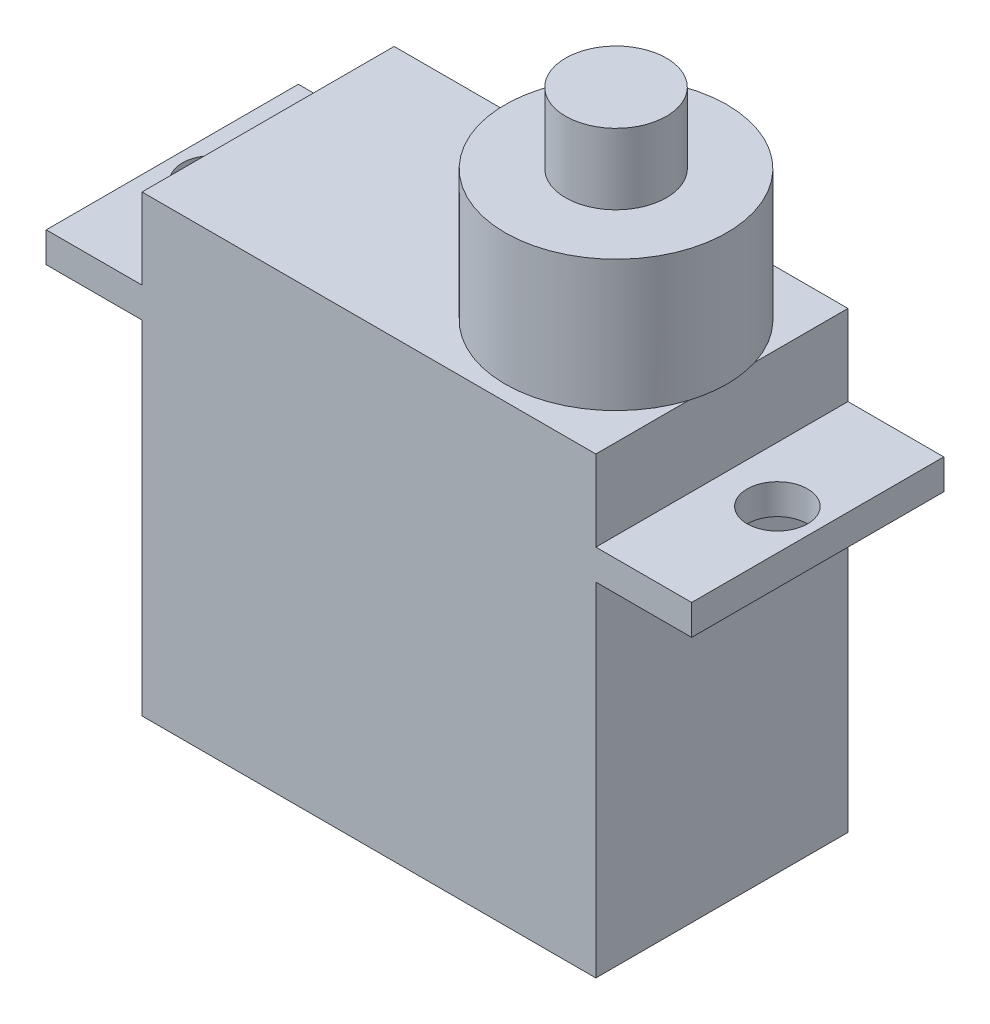
SolidWorks part; units mm, degrees
ref_plane "前视基准面" through (0, 0, 0) normal (0, 0, 1) x (1, 0, 0)
ref_plane "上视基准面" through (0, 0, 0) normal (0, 1, 0) x (1, 0, 0)
ref_plane "右视基准面" through (0, 0, 0) normal (1, 0, 0) x (0, 0, -1)
sketch "草图1" plane through (0, 0, 0) normal (0, 1, 0) x (1, 0, 0)
  line L1 (0, 0) -> (22.5, 0)
  line L2 (0, 0) -> (0, -12.5)
  line L3 (0, -12.5) -> (22.5, -12.5)
  line L4 (22.5, 0) -> (22.5, -12.5)
  dimension "D1" = 12.5
  dimension "D2" = 22.5
extrude "凸台-拉伸1" add sketch "草图1" along normal blind 17
sketch "草图2" plane through (0, 17, 0) normal (0, 1, 0) x (1, 0, 0)
  line L0 (0, -12.5) -> (22.5, -12.5) construction
  line L1 (-4.75, 0) -> (27.25, 0)
  line L2 (-4.75, 0) -> (-4.75, -12.5)
  line L3 (-4.75, -12.5) -> (27.25, -12.5)
  line L4 (27.25, 0) -> (27.25, -12.5)
  line L5 (-4.75, 0) -> (27.25, -12.5) construction
  line L6 (-4.75, -12.5) -> (27.25, 0) construction
  line L7 (22.5, 0) -> (0, 0) construction
  line L8 (0, -6.25) -> (27.25, -6.25) construction
  line L9 (11.25, 0) -> (11.25, -6.25) construction
  line L10 (0, 0) -> (0, -12.5) construction
  circle A0 centre (-2.75, -6.25) radius 1.5
  circle A2 centre (25.25, -6.25) radius 1.5
  point P0 (11.25, -6.25)
  point P7 (0, 0)
  dimension "D4" = 3
  dimension "D1" = 32
  dimension "D2" = 28
extrude "凸台-拉伸2" add sketch "草图2" along normal blind 1.5
sketch "草图3" plane through (0, 18.5, 0) normal (0, 1, 0) x (1, 0, 0)
  line L0 (22.5, 0) -> (0, 0) construction
  line L1 (0, 0) -> (22.5, 0)
  line L2 (0, 0) -> (0, -12.5)
  line L3 (0, -12.5) -> (22.5, -12.5)
  line L4 (22.5, 0) -> (22.5, -12.5)
  line L5 (0, 0) -> (22.5, -12.5) construction
  line L6 (0, -12.5) -> (22.5, 0) construction
  line L7 (22.5, -12.5) -> (22.5, 0) construction
  line L8 (0, 0) -> (0, -12.5) construction
  line L9 (0, -12.5) -> (22.5, -12.5) construction
  point P0 (11.25, -6.25)
extrude "凸台-拉伸3" add sketch "草图3" along normal offset from surface (4 mm away) 22.5 up to face at (11.25, 0, 6.25)
sketch "草图4" plane through (0, 22.5, 0) normal (0, 1, 0) x (1, 0, 0)
  line L1 (25.25, -6.25) -> (25.25, 1.0452) construction
  circle A0 centre (17.25, -6.25) radius 5.5
  dimension "D2" = 11
  dimension "D1" = 8
extrude "凸台-拉伸4" add sketch "草图4" along normal offset from surface (6.5 mm away) 29 up to face at (11.25, 0, 6.25)
sketch "草图5" plane through (0, 29, 0) normal (0, 1, 0) x (1, 0, 0)
  circle A0 centre (17.25, -6.25) radius 2.5
  dimension "D1" = 5
extrude "凸台-拉伸5" add sketch "草图5" along normal blind 3.5
